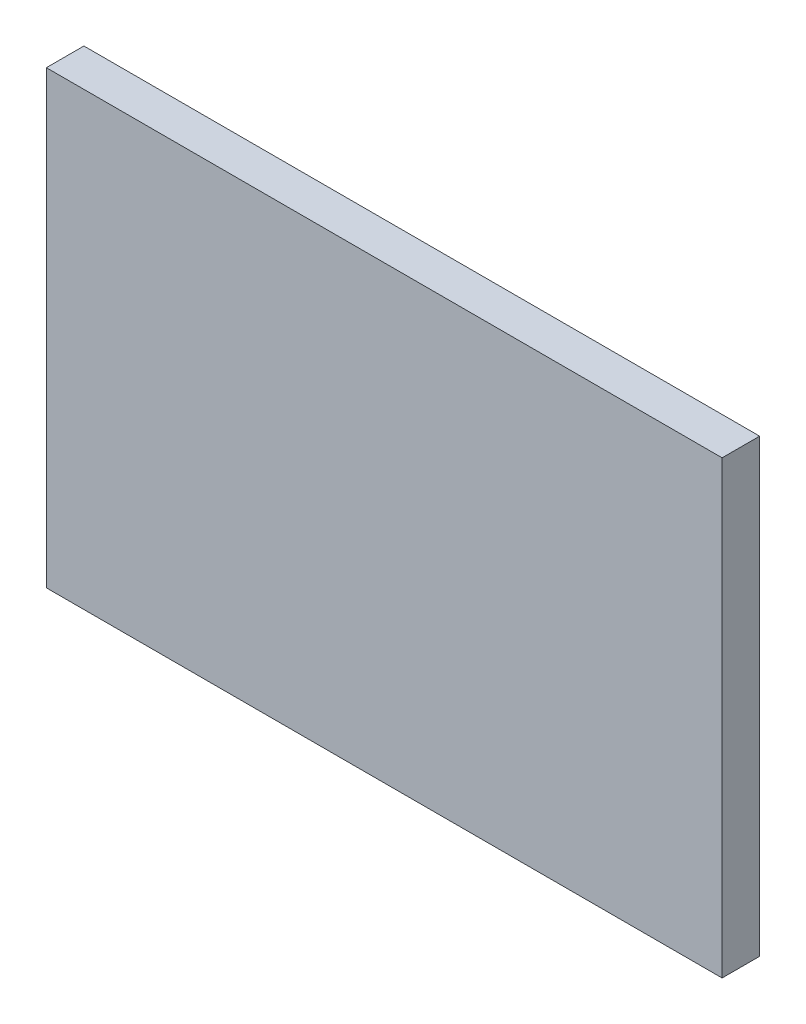
SolidWorks part; units mm, degrees
ref_plane "Front Plane" through (0, 0, 0) normal (0, 0, 1) x (1, 0, 0)
ref_plane "Top Plane" through (0, 0, 0) normal (0, 1, 0) x (1, 0, 0)
ref_plane "Right Plane" through (0, 0, 0) normal (1, 0, 0) x (0, 0, -1)
sketch "Sketch1" plane through (0, 0, 0) normal (0, 0, 1) x (1, 0, 0)
  line L1 (-126.988, 48.4337) -> (-36.988, 48.4337)
  line L2 (-126.988, 48.4337) -> (-126.988, -11.5663)
  line L3 (-126.988, -11.5663) -> (-36.988, -11.5663)
  line L4 (-36.988, 48.4337) -> (-36.988, -11.5663)
  dimension "D1" = 60
  dimension "D2" = 90
extrude "Boss-Extrude1" add sketch "Sketch1" along normal blind 5
